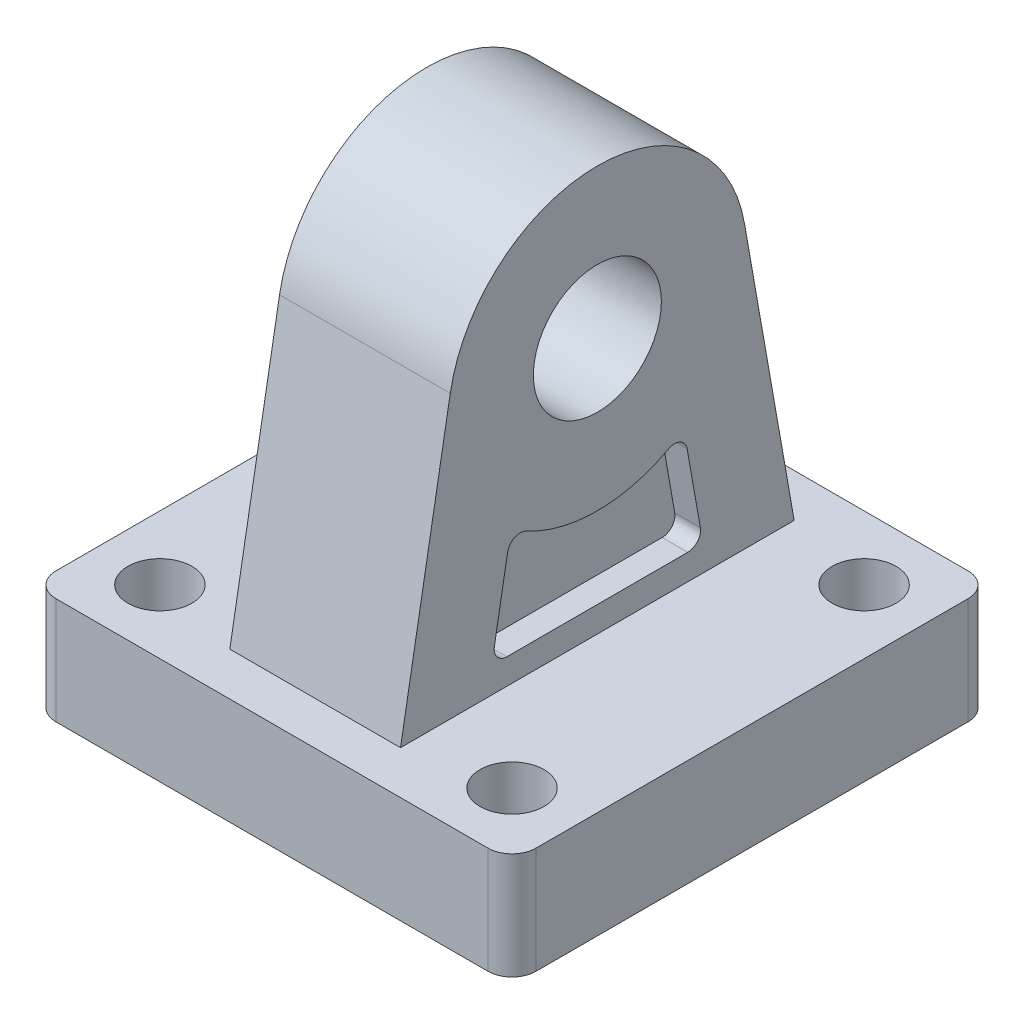
SolidWorks part; units mm, degrees
ref_plane "前视基准面" through (0, 0, 0) normal (0, 0, 1) x (1, 0, 0)
ref_plane "上视基准面" through (0, 0, 0) normal (0, 1, 0) x (1, 0, 0)
ref_plane "右视基准面" through (0, 0, 0) normal (1, 0, 0) x (0, 0, -1)
sketch "草图1" plane through (0, 0, 0) normal (0, 1, 0) x (1, 0, 0)
  line L0 (-8, 0) -> (8, 0) construction
  line L1 (22.5, -22.5) -> (-22.5, -22.5)
  line L2 (22.5, -22.5) -> (22.5, 22.5)
  line L3 (22.5, 22.5) -> (-22.5, 22.5)
  line L4 (-22.5, -22.5) -> (-22.5, 22.5)
  line L5 (22.5, -22.5) -> (-22.5, 22.5) construction
  line L6 (22.5, 22.5) -> (-22.5, -22.5) construction
  line L7 (0, 0) -> (0, 22.5) construction
  circle A0 centre (-16.5, 16.5) radius 3
  point P0 (0, 0)
  point P10 (-16.5, 16.5)
  dimension "缸体L" = 6
  dimension "S" = 45
  dimension "DQ" = 16
  dimension "T" = 33
sketch "草图2" plane through (0, 0, 0) normal (1, 0, 0) x (0, 0, -1)
  line L0 (0, 0) -> (0, 34) construction
  line L1 (0, 34) -> (0, 48) construction
  circle A0 centre (0, 34) radius 6
  point P3 (0, 10)
  dimension "DE" = 12
  dimension "DC" = 34
  dimension "DJ" = 10
  dimension "DD" = 48
sketch "草图3" plane through (0, 0, 0) normal (0, 1, 0) x (1, 0, 0)
  line L0 (-22.5, -22.5) -> (-22.5, 22.5) construction
  line L1 (22.5, 22.5) -> (-22.5, 22.5) construction
  line L2 (22.5, -22.5) -> (22.5, 22.5) construction
  line L3 (22.5, -22.5) -> (-22.5, -22.5) construction
  line L4 (-22.5, -22.5) -> (-22.5, 22.5)
  line L5 (22.5, 22.5) -> (-22.5, 22.5)
  line L6 (22.5, -22.5) -> (22.5, 22.5)
  line L7 (22.5, -22.5) -> (-22.5, -22.5)
extrude "凸台-拉伸1" add sketch "草图3" along normal up to vertex (10 mm away) up to point (0, 10, 0)
sketch "草图4" plane through (0, 0, 0) normal (1, 0, 0) x (0, 0, -1)
  line L0 (-13.7873, 36.4311) -> (-18.4478, 10)
  line L1 (-22.5, 10) -> (22.5, 10) construction
  line L2 (13.7873, 36.4311) -> (18.4478, 10)
  line L3 (0, 34) -> (0, 10) construction
  line L4 (-18.4478, 10) -> (18.4478, 10)
  arc A0 (13.7873, 36.4311) -> (-13.7873, 36.4311) centre (0, 34) ccw
  dimension "D1" = 20
extrude "凸台-拉伸2" add sketch "草图4" along normal up to vertex (8 mm away) from vertex at -8 starting at point (-8, 0, 0)
sketch "草图5" plane through (8, 0, 0) normal (1, 0, 0) x (0, 0, -1)
  circle A0 centre (0, 34) radius 6 construction
  circle A1 centre (0, 34) radius 6
extrude "切除-拉伸1" cut sketch "草图5" against normal through all
sketch "草图8" plane through (8, 0, 0) normal (1, 0, 0) x (0, 0, -1)
  line L0 (-8.1053, 22.5849) -> (-9.9012, 12.4)
  line L4 (0, 0) -> (0, 10) construction
  line L8 (-9.9012, 12.4) -> (9.9012, 12.4)
  line L9 (-13.7873, 36.4311) -> (-18.4478, 10) construction
  line L10 (8.1053, 22.5849) -> (9.9012, 12.4)
  arc A0 (-8.1053, 22.5849) -> (8.1053, 22.5849) centre (0, 34) ccw
  arc A1 (13.7873, 36.4311) -> (-13.7873, 36.4311) centre (0, 34) ccw construction
  circle A4 centre (0, 34) radius 6 construction
  dimension "D2" = 2.4
extrude "切除-拉伸3" cut sketch "草图8" against normal blind 2.4
mirror "镜向3" about plane through (0, 0, 0) normal (1, 0, 0) of "切除-拉伸3"
sketch "草图7" plane through (0, 10, 0) normal (0, 1, 0) x (1, 0, 0)
  circle A0 centre (-16.5, 16.5) radius 3 construction
  circle A1 centre (-16.5, 16.5) radius 3
extrude "切除-拉伸2" cut sketch "草图7" against normal through all
mirror "镜向1" about plane through (0, 0, 0) normal (1, 0, 0) of "切除-拉伸2"
mirror "镜向2" about plane through (0, 0, 0) normal (0, 0, 1) of "镜向1", "切除-拉伸2"
fillet "圆角1" radius 2.25 4 edges at (-22.5, 5, -22.5) (22.5, 5, -22.5) (22.5, 5, 22.5) (-22.5, 5, 22.5)
fillet "圆角2" radius 1.2 8 edges at (-6.8, 12.4, -9.9012) (-6.8, 12.4, 9.9012) (-6.8, 22.5849, 8.1053) (-6.8, 22.5849, -8.1053) (6.8, 22.5849, 8.1053) (6.8, 22.5849, -8.1053) (6.8, 12.4, -9.9012) (6.8, 12.4, 9.9012)
equation "\"D1@圆角1\" =  \"S@草图1\"*0.05"
equation "\"D2@草图8\" =  ( \"DC@草图2\"-\"DJ@草图2\" ) *0.1"
equation "\"D1@切除-拉伸3\" = \"DQ@草图1\"*0.15"
equation "\"D1@圆角2\" = \"DE@草图2\"*0.1"
